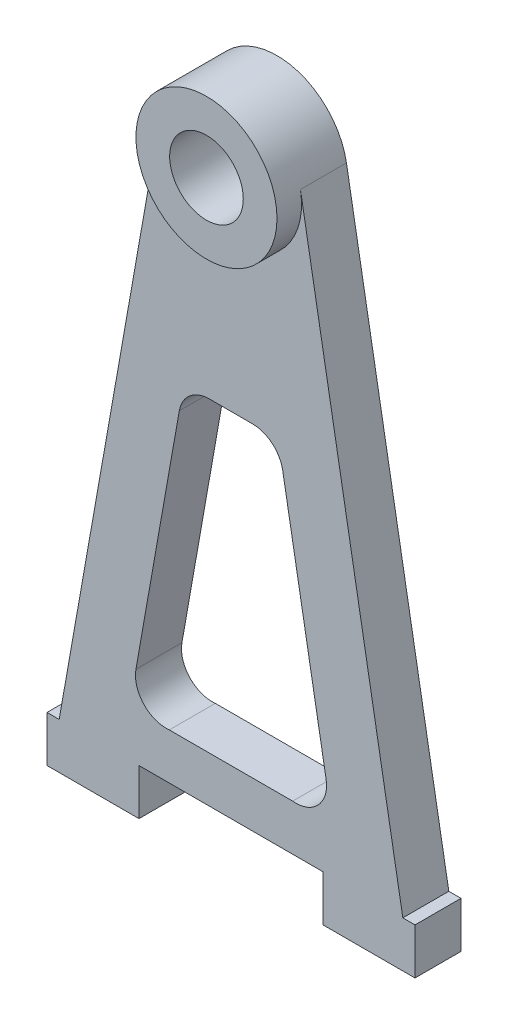
SolidWorks part; units mm, degrees
ref_plane "Front Plane" through (0, 0, 0) normal (0, 0, 1) x (1, 0, 0)
ref_plane "Top Plane" through (0, 0, 0) normal (0, 1, 0) x (1, 0, 0)
ref_plane "Right Plane" through (0, 0, 0) normal (1, 0, 0) x (0, 0, -1)
sketch "Sketch1" plane through (0, 0, 0) normal (0, 0, 1) x (1, 0, 0)
  line L0 (-7.6888, 14.0583) -> (-24.3779, -80.4417)
  line L1 (-26.364, -87.9417) -> (33.636, -87.9417)
  line L2 (14.9607, 14.0583) -> (31.6498, -80.4417)
  line L3 (-7.6888, 14.0583) -> (14.9607, 14.0583) construction
  line L4 (-26.364, -87.9417) -> (-26.364, -80.4417)
  line L5 (-26.364, -80.4417) -> (-24.3779, -80.4417)
  line L6 (33.636, -80.4417) -> (33.636, -87.9417)
  line L7 (31.6498, -80.4417) -> (33.636, -80.4417)
  line L8 (-24.3779, -80.4417) -> (31.6498, -80.4417) construction
  line L9 (3.636, -80.4417) -> (3.636, -87.9417) construction
  line L10 (-4.7979, -27.0722) -> (-11.8669, -67.0996)
  line L12 (19.1388, -67.0996) -> (12.0698, -27.0722)
  line L13 (7.146, -22.9417) -> (0.1259, -22.9417)
  line L15 (-6.4204, -72.9417) -> (13.6923, -72.9417)
  circle A0 centre (3.636, 12.0583) radius 6
  arc A1 (14.9607, 14.0583) -> (-7.6888, 14.0583) centre (3.636, 12.0583) ccw
  arc A2 (13.6923, -72.9417) -> (19.1388, -67.0996) centre (14.215, -67.9691) ccw
  arc A3 (-11.8669, -67.0996) -> (-6.4204, -72.9417) centre (-6.9431, -67.9691) ccw
  arc A4 (12.0698, -27.0722) -> (7.146, -22.9417) centre (7.146, -27.9417) ccw
  arc A5 (-4.7979, -27.0722) -> (0.1259, -22.9417) centre (0.1259, -27.9417) cw
  dimension "D1" = 12
  dimension "D2" = 23
  dimension "D9" = 5
  dimension "D3" = 2
  dimension "D4" = 100
  dimension "D5" = 7.5
  dimension "D6" = 60
  dimension "D7" = 10
  dimension "D8" = 10
  dimension "D10" = 15
  dimension "D11" = 50
extrude "Boss-Extrude1" add sketch "Sketch1" along normal blind 7.5 contours L0 L5 L4 L1 L6 L7 L2 A1
sketch "Sketch2" plane through (0, 0, 7.5) normal (0, 0, 1) x (1, 0, 0)
  circle A0 centre (3.636, 12.0583) radius 11.5
  circle A1 centre (3.636, 12.0583) radius 6
extrude "Boss-Extrude2" add sketch "Sketch2" along normal blind 4 contours A0
sketch "Sketch3" plane through (0, 0, 7.5) normal (0, 0, 1) x (1, 0, 0)
  line L0 (-26.364, -87.9417) -> (33.636, -87.9417) construction
  line L1 (-11.364, -87.9417) -> (18.636, -87.9417)
  line L2 (-11.364, -87.9417) -> (-11.364, -80.4417)
  line L3 (-11.364, -80.4417) -> (18.636, -80.4417)
  line L4 (18.636, -87.9417) -> (18.636, -80.4417)
  line L5 (-26.364, -80.4417) -> (-26.364, -87.9417) construction
  line L6 (33.636, -87.9417) -> (33.636, -80.4417) construction
  dimension "D1" = 15
  dimension "D2" = 15
  dimension "D3" = 7.5
extrude "Cut-Extrude1" cut sketch "Sketch3" against normal blind 17 contours L3 L4 L1 L2
